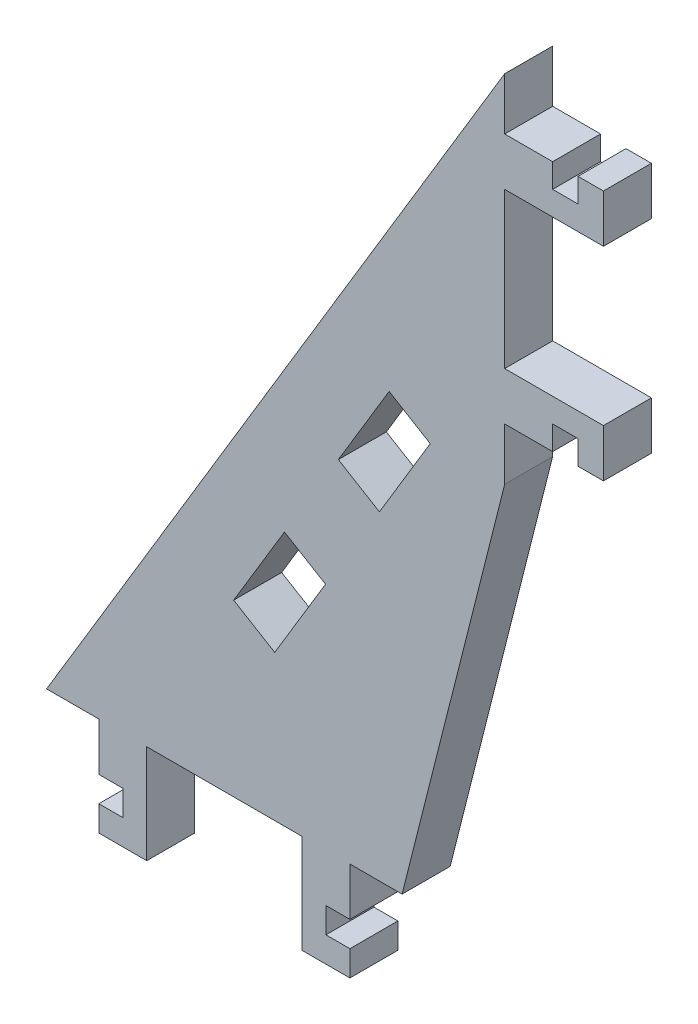
SolidWorks part; units mm, degrees
ref_plane "Front Plane" through (0, 0, 0) normal (0, 0, 1) x (1, 0, 0)
ref_plane "Top Plane" through (0, 0, 0) normal (0, 1, 0) x (1, 0, 0)
ref_plane "Right Plane" through (0, 0, 0) normal (1, 0, 0) x (0, 0, -1)
sketch "Sketch1" plane through (0, 0, 0) normal (0, 0, 1) x (1, 0, 0)
  line L0 (28.6385, 47.625) -> (28.6385, 41.0972)
  line L1 (28.6385, 3.175) -> (15.8115, -47.625)
  line L2 (15.8115, -47.625) -> (9.2837, -47.625)
  line L3 (-28.6385, -47.625) -> (28.6385, 47.625)
  line L4 (28.6385, 35.1028) -> (40.9829, 35.1028)
  line L5 (40.9829, 35.1028) -> (40.9829, 41.0972)
  line L6 (40.9829, 41.0972) -> (37.8079, 41.0972)
  line L7 (37.8079, 41.0972) -> (37.8079, 38.1)
  line L8 (37.8079, 38.1) -> (34.6329, 38.1)
  line L9 (34.6329, 38.1) -> (34.6329, 41.0972)
  line L10 (34.6329, 41.0972) -> (28.6385, 41.0972)
  line L11 (28.6385, 25.4) -> (93.7621, 25.4) construction
  line L12 (34.6329, 9.7028) -> (28.6385, 9.7028)
  line L13 (34.6329, 12.7) -> (34.6329, 9.7028)
  line L14 (37.8079, 12.7) -> (34.6329, 12.7)
  line L15 (37.8079, 9.7028) -> (37.8079, 12.7)
  line L16 (40.9829, 9.7028) -> (37.8079, 9.7028)
  line L17 (40.9829, 15.6972) -> (40.9829, 9.7028)
  line L18 (28.6385, 15.6972) -> (40.9829, 15.6972)
  line L19 (-6.4135, -47.625) -> (-6.4135, -79.0493) construction
  line L20 (-22.1107, -47.625) -> (-22.1107, -53.6194)
  line L21 (-22.1107, -53.6194) -> (-19.1135, -53.6194)
  line L22 (-19.1135, -53.6194) -> (-19.1135, -56.7944)
  line L23 (-19.1135, -56.7944) -> (-22.1107, -56.7944)
  line L24 (-22.1107, -56.7944) -> (-22.1107, -59.9694)
  line L25 (-22.1107, -59.9694) -> (-16.1163, -59.9694)
  line L26 (-16.1163, -59.9694) -> (-16.1163, -47.625)
  line L27 (3.2893, -59.9694) -> (3.2893, -47.625)
  line L28 (9.2837, -59.9694) -> (3.2893, -59.9694)
  line L29 (9.2837, -56.7944) -> (9.2837, -59.9694)
  line L30 (6.2865, -56.7944) -> (9.2837, -56.7944)
  line L31 (6.2865, -53.6194) -> (6.2865, -56.7944)
  line L32 (9.2837, -53.6194) -> (6.2865, -53.6194)
  line L33 (9.2837, -47.625) -> (9.2837, -53.6194)
  line L34 (-22.1107, -47.625) -> (-28.6385, -47.625)
  line L35 (3.2893, -47.625) -> (-16.1163, -47.625)
  line L36 (28.6385, 9.7028) -> (28.6385, 3.175)
  line L37 (28.6385, 35.1028) -> (28.6385, 15.6972)
  point P2 (0, 0)
  point P42 (0, 0)
  dimension "D1" = 44.45
  dimension "D2" = 5.9944
  dimension "D3" = 3.175
  dimension "D4" = 3.175
  dimension "D5" = 5.9944
  dimension "D6" = 2.9972
  dimension "D7" = 25.4
  dimension "D8" = 57.3278
  dimension "D9" = 5.9944
  dimension "D10" = 3.175
  dimension "D11" = 3.175
  dimension "D12" = 2.9972
  dimension "D13" = 5.9944
  dimension "D14" = 25.4
  dimension "D15" = 19.3548
  dimension "D16" = 44.45
extrude "Boss-Extrude1" add sketch "Sketch1" along normal blind 6
sketch "Sketch2" plane through (0, 0, 6) normal (0, 0, 1) x (1, 0, 0)
  line L0 (28.6385, 24.2131) -> (-14.5601, -47.625) construction
  line L1 (28.6385, 15.6972) -> (28.6385, 35.1028) construction
  line L2 (-16.1163, -47.625) -> (3.2893, -47.625) construction
  line L3 (28.6385, 47.625) -> (-28.6385, -47.625) construction
  line L4 (14.1896, 6.001) -> (7.8412, -4.5563)
  line L5 (7.8412, -4.5563) -> (12.9783, -7.6454)
  line L6 (12.9783, -7.6454) -> (19.3267, 2.9118)
  line L7 (19.3267, 2.9118) -> (14.1896, 6.001)
  line L8 (7.8412, -4.5563) -> (19.3267, 2.9118) construction
  line L9 (14.1896, 6.001) -> (12.9783, -7.6454) construction
  line L10 (1.1001, -15.7665) -> (6.2372, -18.8557)
  line L11 (6.2372, -18.8557) -> (-0.1112, -29.4129)
  line L12 (-0.1112, -29.4129) -> (-5.2484, -26.3238)
  line L13 (-5.2484, -26.3238) -> (1.1001, -15.7665)
  line L15 (7.8412, -4.5563) -> (1.1001, -15.7665) construction
  line L16 (7.0392, -11.706) -> (4.4706, -10.1614) construction
  point P8 (13.5839, -0.8222)
  dimension "D1" = 5.9944
  dimension "D2" = 12.319
  dimension "D3" = 12.065
  dimension "D4" = 12.319
  dimension "D5" = 5.9944
  dimension "D6" = 13.081
extrude "Cut-Extrude1" cut sketch "Sketch2" against normal through all
